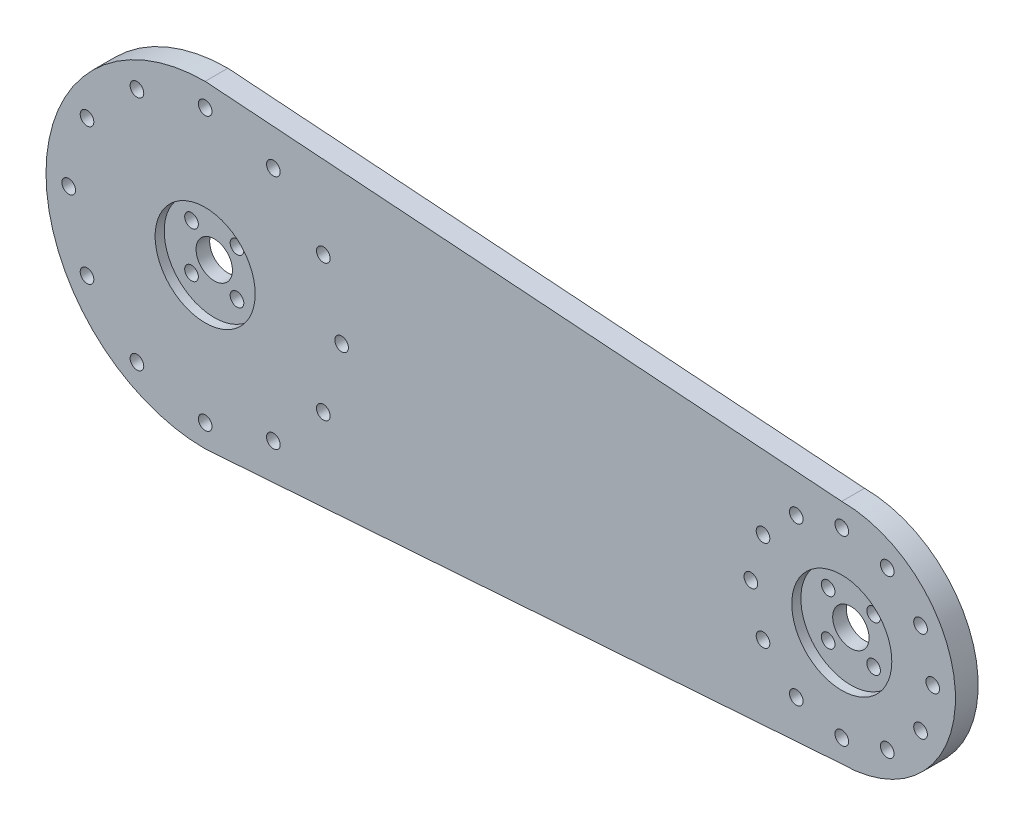
SolidWorks part; units mm, degrees
ref_plane "前视基准面" through (0, 0, 0) normal (0, 0, 1) x (1, 0, 0)
ref_plane "上视基准面" through (0, 0, 0) normal (0, 1, 0) x (1, 0, 0)
ref_plane "右视基准面" through (0, 0, 0) normal (1, 0, 0) x (0, 0, -1)
other "Configuration Table"
sketch "草图1" plane through (0, 0, 0) normal (0, 0, 1) x (1, 0, 0)
  line L0 (0, 0) -> (140, 0)
  line L1 (0, 35) -> (140, 25)
  line L2 (0, -35) -> (140, -25)
  circle A0 centre (0, 0) radius 35
  circle A1 centre (140, 0) radius 25
  dimension "D1" = 70
  dimension "D3" = 50
  dimension "D2" = 140
extrude "凸台-拉伸3" add sketch "草图1" along normal blind 5
sketch "草图4" plane through (0, 0, 5) normal (0, 0, 1) x (1, 0, 0)
  line L1 (-5, -5) -> (5, -5)
  line L2 (-5, -5) -> (-5, 5)
  line L3 (-5, 5) -> (5, 5)
  line L4 (5, -5) -> (5, 5)
  line L5 (-5, -5) -> (5, 5) construction
  line L6 (-5, 5) -> (5, -5) construction
  line L7 (135, -5) -> (145, -5)
  line L8 (135, -5) -> (135, 5)
  line L9 (135, 5) -> (145, 5)
  line L10 (145, -5) -> (145, 5)
  line L11 (135, -5) -> (145, 5) construction
  line L12 (135, 5) -> (145, -5) construction
  circle A0 centre (0, 0) radius 4
  circle A1 centre (-5, 5) radius 1.5
  circle A2 centre (5, 5) radius 1.5
  circle A3 centre (5, -5) radius 1.5
  circle A4 centre (-5, -5) radius 1.5
  circle A5 centre (140, 0) radius 4
  circle A6 centre (135, 5) radius 1.5
  circle A7 centre (145, 5) radius 1.5
  circle A8 centre (145, -5) radius 1.5
  circle A9 centre (135, -5) radius 1.5
  dimension "D1" = 8
  dimension "D4" = 3
  dimension "D6" = 8
  dimension "D9" = 3
  dimension "D2" = 10
  dimension "D3" = 10
  dimension "D7" = 10
  dimension "D8" = 10
  dimension "D5" = 4
  dimension "D10" = 4
extrude "切除-拉伸3" cut sketch "草图4" against normal blind 5 contours A5 | A0 | L2 A4 L1 | L1 A4 L2 | A6 | A9 | A8 | A7 | A1 | A2 | A3
sketch "草图5" plane through (0, 0, 5) normal (0, 0, 1) x (1, 0, 0)
  circle A0 centre (0, 0) radius 11
  circle A1 centre (140, 0) radius 11
  dimension "D1" = 22
  dimension "D2" = 22
extrude "切除-拉伸4" cut sketch "草图5" against normal blind 2
sketch "草图6" plane through (0, 0, 5) normal (0, 0, 1) x (1, 0, 0)
  circle A0 centre (0, 0) radius 30
  circle A1 centre (0, 30) radius 1.5
  circle A2 centre (15, 25.9808) radius 1.5
  circle A3 centre (25.9808, 15) radius 1.5
  circle A4 centre (30, 0) radius 1.5
  circle A5 centre (25.9808, -15) radius 1.5
  circle A6 centre (15, -25.9808) radius 1.5
  circle A7 centre (0, -30) radius 1.5
  circle A8 centre (-15, -25.9808) radius 1.5
  circle A9 centre (-25.9808, -15) radius 1.5
  circle A10 centre (-30, 0) radius 1.5
  circle A11 centre (-25.9808, 15) radius 1.5
  circle A12 centre (-15, 25.9808) radius 1.5
  circle A13 centre (140, 0) radius 20
  circle A14 centre (140, 20) radius 1.5
  circle A15 centre (150, 17.3205) radius 1.5
  circle A16 centre (157.3205, 10) radius 1.5
  circle A17 centre (160, 0) radius 1.5
  circle A18 centre (157.3205, -10) radius 1.5
  circle A19 centre (150, -17.3205) radius 1.5
  circle A20 centre (140, -20) radius 1.5
  circle A21 centre (130, -17.3205) radius 1.5
  circle A22 centre (122.6795, -10) radius 1.5
  circle A23 centre (120, 0) radius 1.5
  circle A24 centre (122.6795, 10) radius 1.5
  circle A25 centre (130, 17.3205) radius 1.5
  point P29 (0, 0)
  dimension "D1" = 60
  dimension "D2" = 3
  dimension "D4" = 40
  dimension "D5" = 3
  dimension "D3" = 12
  dimension "D6" = 12
extrude "切除-拉伸6" cut sketch "草图6" against normal through all contours A0 A12 | A11 | A1 | A2 | A3 | A4 | A5 | A6 | A7 | A8 | A9 | A10 | A25 | A14 | A15 | A16 | A17 | A18 | A19 | A20 | A21 | A22 | A23 | A24
